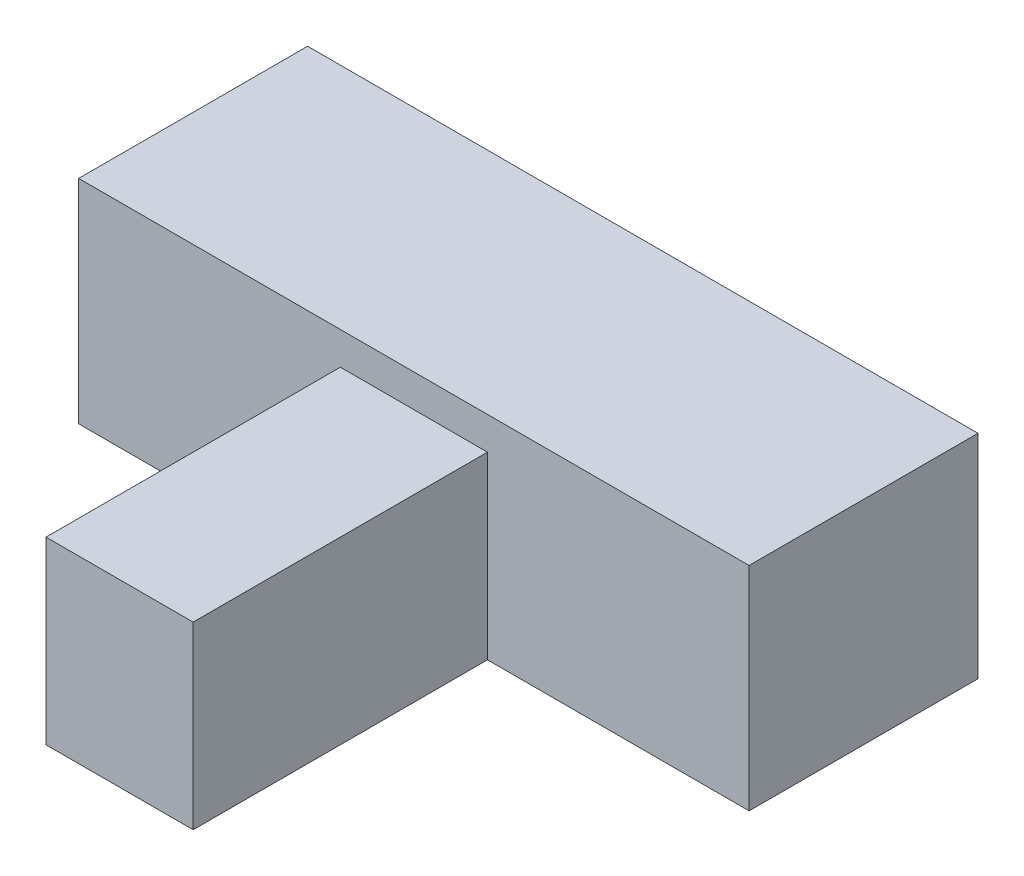
SolidWorks part; units mm, degrees
ref_plane "Front Plane" through (0, 0, 0) normal (0, 0, 1) x (1, 0, 0)
ref_plane "Top Plane" through (0, 0, 0) normal (0, 1, 0) x (1, 0, 0)
ref_plane "Right Plane" through (0, 0, 0) normal (1, 0, 0) x (0, 0, -1)
sketch "Sketch1" plane through (0, 0, 0) normal (0, 0, 1) x (1, 0, 0)
  line L1 (0, 0) -> (45, 0)
  line L2 (0, 0) -> (0, 55)
  line L3 (0, 55) -> (45, 55)
  line L4 (45, 0) -> (45, 55)
  dimension "D1" = 55
  dimension "D2" = 45
extrude "Boss-Extrude1" add sketch "Sketch1" along normal blind 165 contours L3 L4 L1 L2
sketch "Sketch2" plane through (0, 0, 0) normal (0, 0, -1) x (-1, 0, 0)
  line L0 (0, 0) -> (80, 0)
  line L5 (80, 0) -> (80, 80)
  line L6 (80, 80) -> (-125, 80)
  line L7 (-125, 80) -> (-125, 0)
  line L9 (-125, 0) -> (-45, 0)
  line L10 (-45, 0) -> (0, 0)
  dimension "D2" = 80
  dimension "D3" = 80
  dimension "D1" = 80
extrude "Boss-Extrude2" add sketch "Sketch2" against normal blind 75 contours L5 L6 L7 L9 L10 L0
sketch "Sketch3" plane through (0, 0, 0) normal (0, 0, -1) x (-1, 0, 0)
  line L4 (-125, 0) -> (80, 0)
  line L5 (80, 0) -> (80, 80)
  line L6 (80, 80) -> (-125, 80)
  line L7 (-125, 80) -> (-125, 0)
  line L8 (-125, 0) -> (80, 0)
  line L9 (80, 0) -> (80, 80)
  line L10 (80, 80) -> (-125, 80)
  line L11 (-125, 80) -> (-125, 0)
  dimension "D1" = 0
extrude "Cut-Extrude1" cut sketch "Sketch3" against normal blind 5
sketch "Sketch4" plane through (0, 80, 0) normal (0, 1, 0) x (1, 0, 0)
  line L4 (125, -75) -> (125, -5)
  line L5 (125, -5) -> (-80, -5)
  line L6 (-80, -5) -> (-80, -75)
  line L7 (-80, -75) -> (125, -75)
  line L8 (125, -75) -> (125, -5)
  line L9 (125, -5) -> (-80, -5)
  line L10 (-80, -5) -> (-80, -75)
  line L11 (-80, -75) -> (125, -75)
  dimension "D1" = 0
extrude "Cut-Extrude2" cut sketch "Sketch4" against normal blind 15
